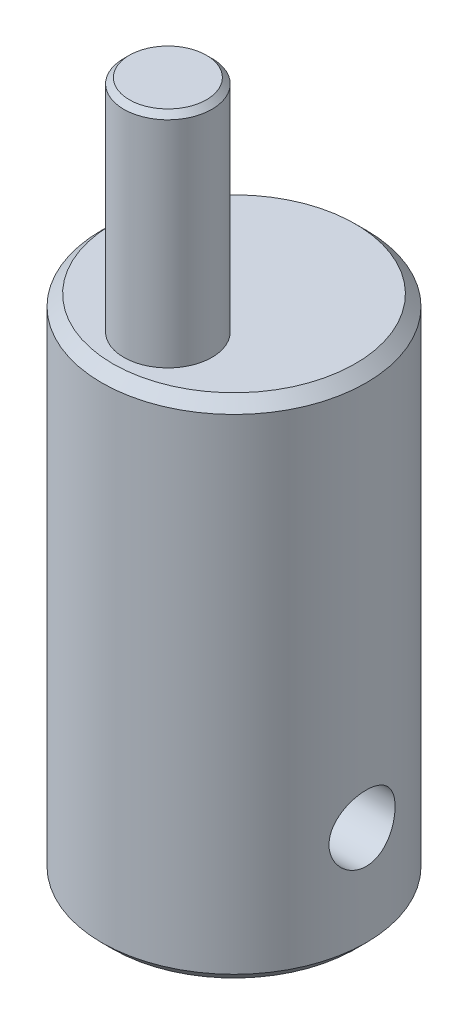
SolidWorks part; units mm, degrees
ref_plane "Front Plane" through (0, 0, 0) normal (0, 0, 1) x (1, 0, 0)
ref_plane "Top Plane" through (0, 0, 0) normal (0, 1, 0) x (1, 0, 0)
ref_plane "Right Plane" through (0, 0, 0) normal (1, 0, 0) x (0, 0, -1)
sketch "Sketch1" plane through (0, 0, 0) normal (0, 1, 0) x (1, 0, 0)
  circle A0 centre (0, 0) radius 6
extrude "Boss-Extrude1" add sketch "Sketch1" along normal blind 23
sketch "Sketch2" plane through (0, 23, 0) normal (0, 1, 0) x (1, 0, 0)
  circle A0 centre (0, -3) radius 2
  dimension "D1" = 3
extrude "Boss-Extrude2" add sketch "Sketch2" along normal blind 10
sketch "Sketch3" plane through (0, 0, 0) normal (1, 0, 0) x (0, 0, -1)
  circle A0 centre (0, 5) radius 1.5
  dimension "D1" = 3
  dimension "D2" = 5
extrude "Cut-Extrude1" cut sketch "Sketch3" against normal through all both and the other way through all
chamfer "Chamfer1" distance 0.25 angle 45 1 edges at (0, 33, 5)
chamfer "Chamfer2" distance 0.5 angle 45 2 edges at (0, 0, 6) (0, 23, 6)
